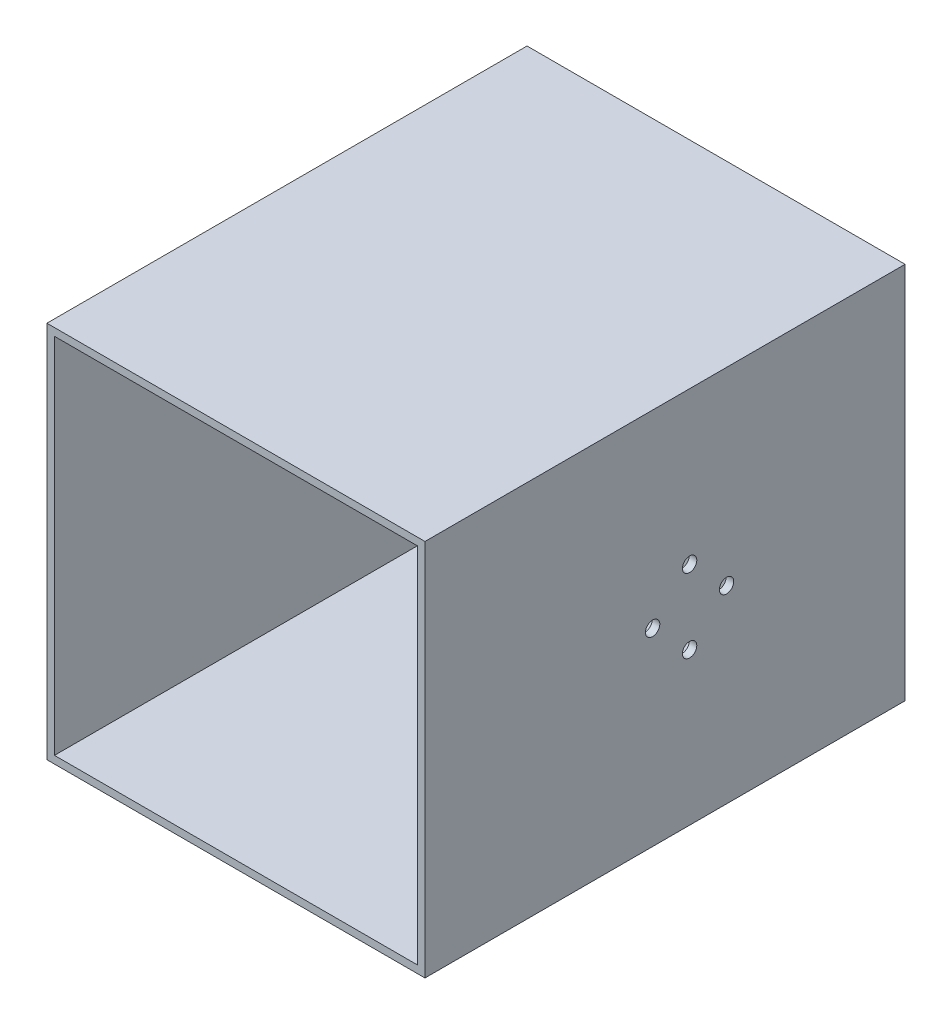
SolidWorks part; units mm, degrees
ref_plane "Front" through (0, 0, 0) normal (0, 0, 1) x (1, 0, 0)
ref_plane "Top" through (0, 0, 0) normal (0, 1, 0) x (1, 0, 0)
ref_plane "Right" through (0, 0, 0) normal (1, 0, 0) x (0, 0, -1)
sketch "Sketch1" plane through (0, 0, 0) normal (0, 0, 1) x (1, 0, 0)
  line L11 (169.2488, 9.5731) -> (69.2488, 9.5731)
  line L12 (169.2488, 9.5731) -> (169.2488, 109.5731)
  line L13 (169.2488, 109.5731) -> (69.2488, 109.5731)
  line L14 (69.2488, 9.5731) -> (69.2488, 109.5731)
  line L15 (169.2488, 9.5731) -> (69.2488, 109.5731) construction
  line L16 (169.2488, 109.5731) -> (69.2488, 9.5731) construction
  point P0 (0, 0)
  point P5 (119.2488, 59.5731)
  point P11 (0, 0)
  dimension "D1" = 100
  dimension "D2" = 100
extrude "Boss-Extrude2" add sketch "Sketch1" along normal blind 2
sketch "Sketch2" plane through (0, 0, 2) normal (0, 0, 1) x (1, 0, 0)
  line L1 (169.2488, 109.5731) -> (69.2488, 109.5731)
  line L2 (169.2488, 109.5731) -> (169.2488, 9.5731)
  line L3 (169.2488, 9.5731) -> (69.2488, 9.5731)
  line L4 (69.2488, 109.5731) -> (69.2488, 9.5731)
  line L5 (71.2488, 107.5731) -> (167.2488, 107.5731)
  line L6 (71.2488, 107.5731) -> (71.2488, 11.5731)
  line L7 (71.2488, 11.5731) -> (167.2488, 11.5731)
  line L8 (167.2488, 107.5731) -> (167.2488, 11.5731)
  dimension "D1" = 2
  dimension "D2" = 2
  dimension "D3" = 2
  dimension "D4" = 2
extrude "Boss-Extrude4" add sketch "Sketch2" along normal blind 125
sketch "Sketch3" plane through (169.2488, 0, 0) normal (1, 0, 0) x (0, 0, -1)
  line L0 (-57, 109.5731) -> (-57, 9.5731) construction
  line L1 (-127, 109.5731) -> (0, 109.5731) construction
  line L2 (-127, 9.5731) -> (0, 9.5731) construction
  line L3 (-91.8221, 59.5731) -> (-22.1779, 59.5731) construction
  line L4 (-127, 9.5731) -> (-127, 109.5731) construction
  line L5 (-57, 59.5731) -> (-57, 69.3521) construction
  circle A0 centre (-57, 69.3521) radius 1.9
  circle A1 centre (-47.221, 59.5731) radius 1.9
  circle A2 centre (-57, 49.7941) radius 1.9
  circle A3 centre (-66.779, 59.5731) radius 1.9
  point P9 (-57, 59.5731)
  point P23 (-57, 59.5731)
  dimension "D3" = 3.8
  dimension "D4" = 4
  dimension "D1" = 70
  dimension "D2" = 9.779
extrude "Cut-Extrude1" cut sketch "Sketch3" against normal through all both and the other way through all
